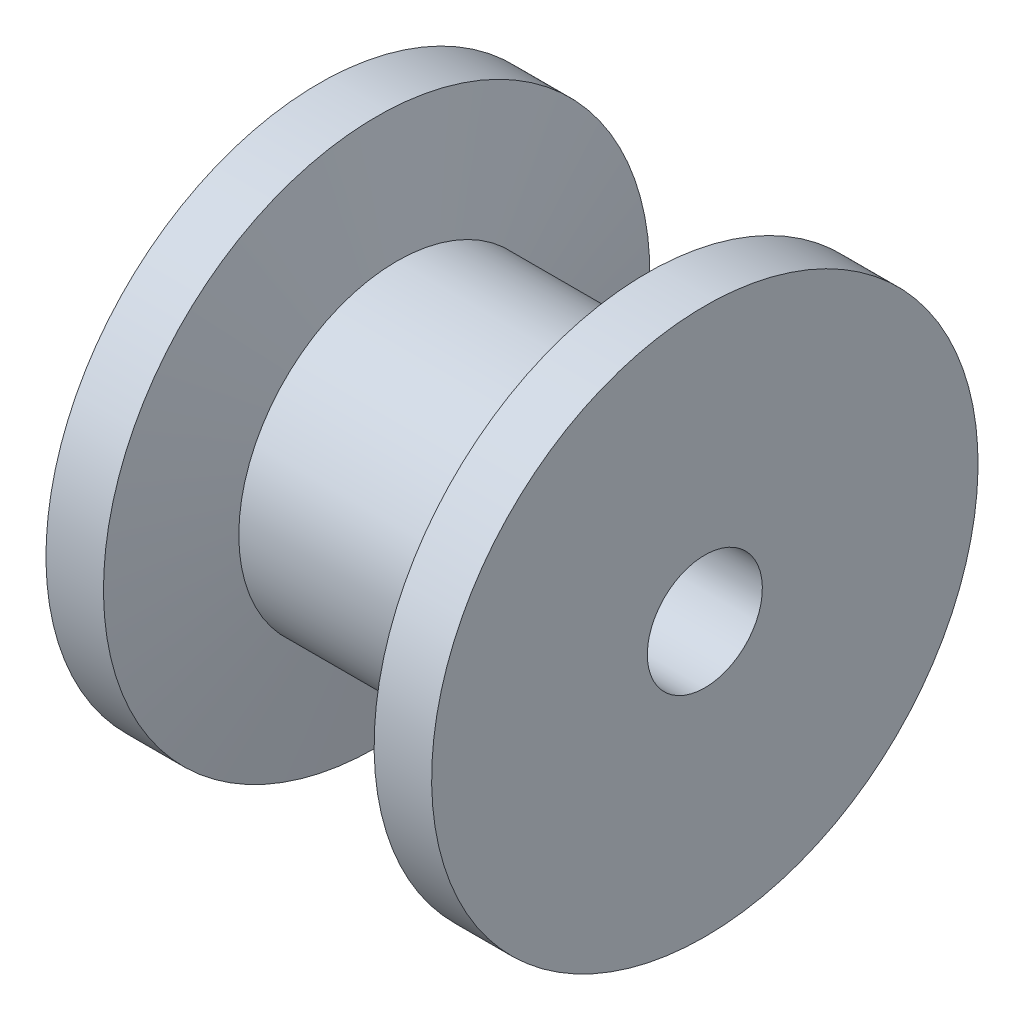
SolidWorks part; units mm, degrees
material "1060 Alloy"
ref_plane "Front Plane" through (0, 0, 0) normal (0, 0, 1) x (1, 0, 0)
ref_plane "Top Plane" through (0, 0, 0) normal (0, 1, 0) x (1, 0, 0)
ref_plane "Right Plane" through (0, 0, 0) normal (1, 0, 0) x (0, 0, -1)
sketch "Sketch1" plane through (0, 0, 0) normal (0, 0, 1) x (1, 0, 0)
  line L1 (-21.4209, 2) -> (-21.4209, 9.5)
  line L4 (-24.1262, 5.5) -> (-32.1262, 5.5)
  line L5 (-32.1262, 5.5) -> (-32.8315, 9.5)
  line L6 (-32.8315, 9.5) -> (-34.8315, 9.5)
  line L7 (-34.8315, 9.5) -> (-34.8315, 3)
  line L9 (-24.1262, 5.5) -> (-23.4209, 9.5)
  line L10 (-23.4209, 9.5) -> (-21.4209, 9.5)
  line L11 (-33.4209, 2) -> (-21.4209, 2)
  line L12 (-33.4209, 2) -> (-33.4209, 0)
  line L16 (-34.8315, 0) -> (2.9375, 0) construction
  line L17 (-33.4209, 0) -> (-34.8315, 0)
  line L18 (-34.8315, 3) -> (-34.8315, 0)
  dimension "D1" = 9.5
  dimension "D2" = 0
  dimension "D3" = 2
  dimension "D4" = 8
  dimension "D5" = 80
  dimension "D6" = 80
  dimension "D7" = 2
  dimension "D9" = 12
  dimension "D12" = 4
revolve "Revolve1" add sketch "Sketch1" angle 360 about L16
